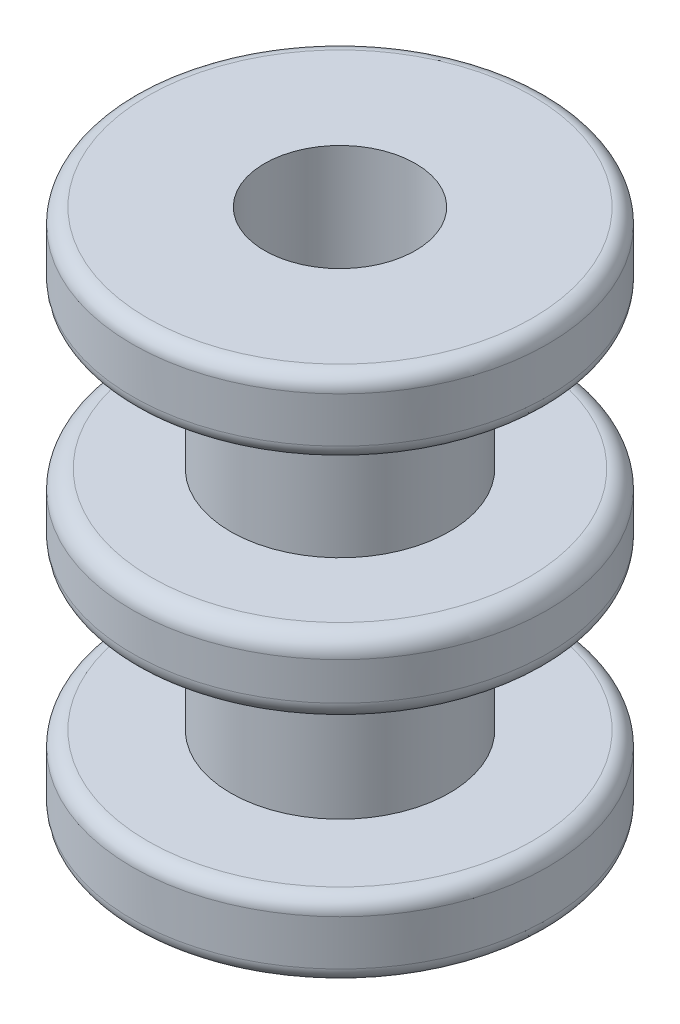
SolidWorks part; units mm, degrees
ref_plane "前视基准面" through (0, 0, 0) normal (0, 0, 1) x (1, 0, 0)
ref_plane "上视基准面" through (0, 0, 0) normal (0, 1, 0) x (1, 0, 0)
ref_plane "右视基准面" through (0, 0, 0) normal (1, 0, 0) x (0, 0, -1)
sketch "草图1" plane through (0, 0, 0) normal (0, 0, 1) x (1, 0, 0)
  line L0 (0, -9.6328) -> (0, 9.6328) construction
  line L1 (-8.4454, 0) -> (8.4454, 0) construction
  line L2 (2, 7) -> (5.5, 7)
  line L3 (5.5, 7) -> (5.5, 5)
  line L4 (5.5, 5) -> (2.9, 5)
  line L5 (2.9, 5) -> (2.9, 1)
  line L6 (2.9, 1) -> (5.5, 1)
  line L7 (5.5, 1) -> (5.5, -1)
  line L8 (2, 7) -> (2, -7)
  line L9 (2.9, -1) -> (5.5, -1)
  line L10 (2.9, -5) -> (2.9, -1)
  line L11 (5.5, -5) -> (2.9, -5)
  line L12 (5.5, -7) -> (5.5, -5)
  line L13 (2, -7) -> (5.5, -7)
  point P4 (0, 0)
  point P8 (0, 0)
  point P16 (2, 0)
  point P17 (5.5, 0)
  dimension "D1" = 2
  dimension "D2" = 5.5
  dimension "D3" = 14
  dimension "D4" = 2.9
  dimension "D5" = 2
  dimension "D6" = 4
revolve "旋转1" add sketch "草图1" angle 360 about L0
fillet "圆角1" radius 0.5 2 edges at (0, -1, -5.5) (0, 1, -5.5)
fillet "圆角2" radius 0.4 4 edges at (0, -7, -5.5) (0, -5, -5.5) (0, 5, -5.5) (0, 7, -5.5)
